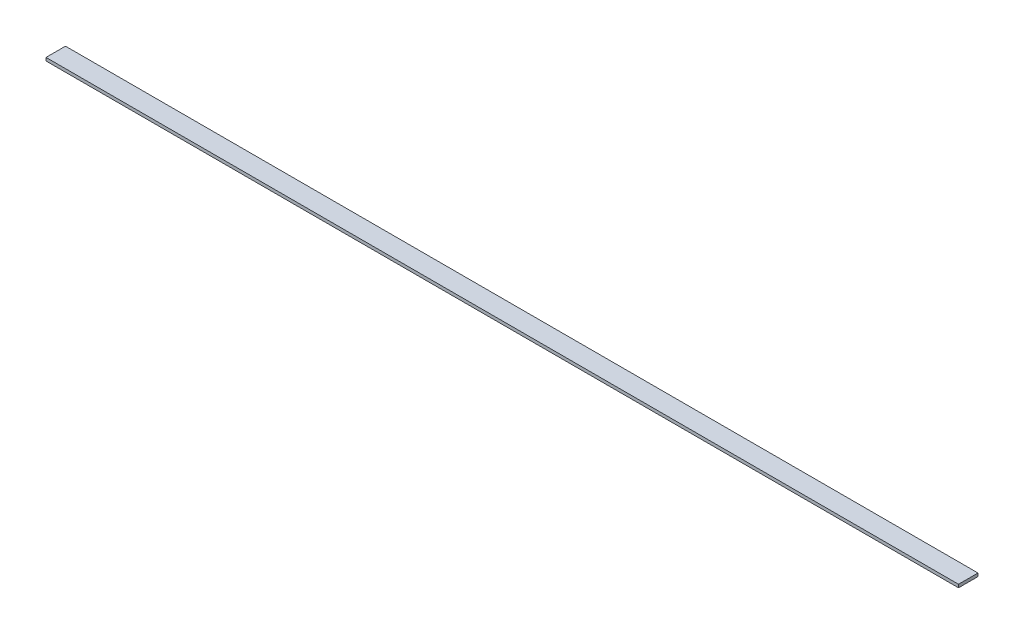
SolidWorks part; units mm, degrees
ref_plane "Front Plane" through (0, 0, 0) normal (0, 0, 1) x (1, 0, 0)
ref_plane "Top Plane" through (0, 0, 0) normal (0, 1, 0) x (1, 0, 0)
ref_plane "Right Plane" through (0, 0, 0) normal (1, 0, 0) x (0, 0, -1)
sketch "Sketch3" plane through (0, 0, 0) normal (1, 0, 0) x (0, 0, -1)
  line L1 (-12.5, 2) -> (12.5, 2)
  line L2 (-12.5, 2) -> (-12.5, -2)
  line L3 (-12.5, -2) -> (12.5, -2)
  line L4 (12.5, 2) -> (12.5, -2)
  line L5 (-12.5, 2) -> (12.5, -2) construction
  line L6 (-12.5, -2) -> (12.5, 2) construction
  point P0 (0, 0)
  dimension "D1" = 25
  dimension "D2" = 4
extrude "Boss-Extrude1" add sketch "Sketch3" along normal up to vertex (505 mm away) and the other way up to vertex (666 mm away)
